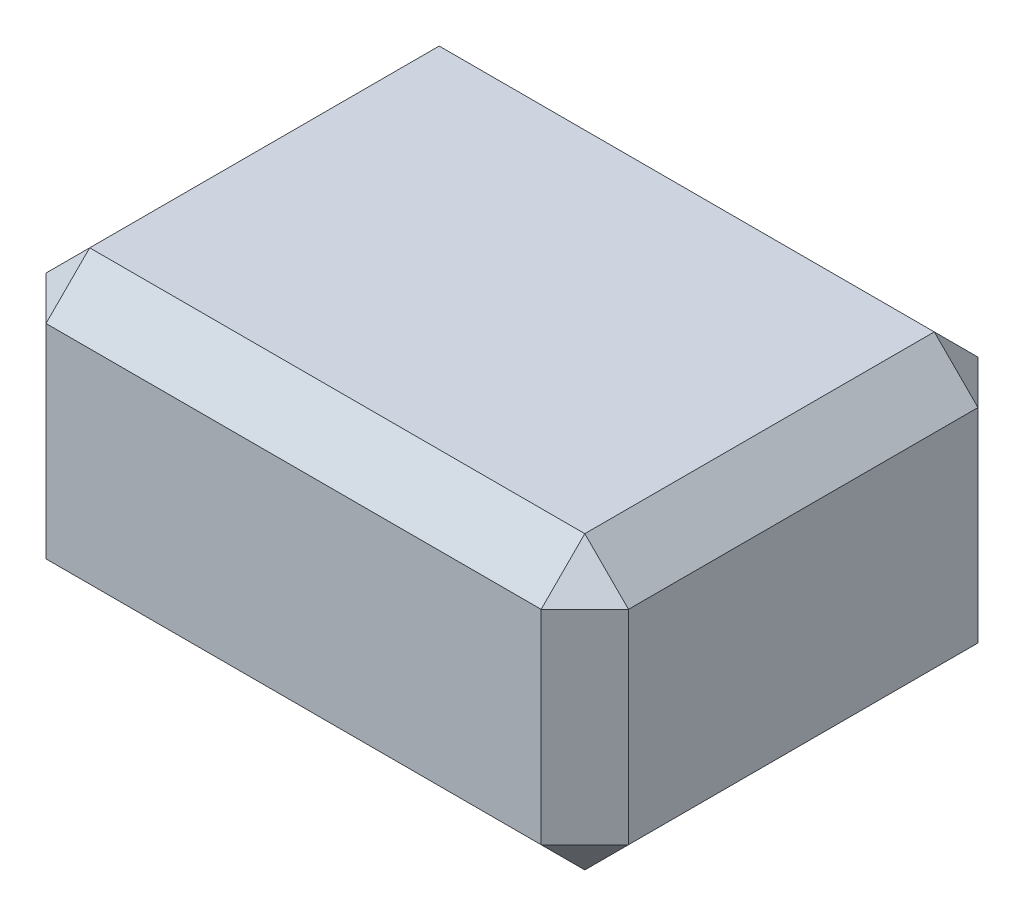
SolidWorks part; units mm, degrees
ref_plane "Front Plane" through (0, 0, 0) normal (0, 0, 1) x (1, 0, 0)
ref_plane "Top Plane" through (0, 0, 0) normal (0, 1, 0) x (1, 0, 0)
ref_plane "Right Plane" through (0, 0, 0) normal (1, 0, 0) x (0, 0, -1)
sketch "Sketch1" plane through (0, 0, 0) normal (0, 1, 0) x (1, 0, 0)
  line L0 (-20, -15) -> (20, -15)
  line L1 (20, -15) -> (20, 15)
  line L2 (20, 15) -> (-20, 15)
  line L3 (-20, 15) -> (-20, -15)
extrude "Boss-Extrude1" add sketch "Sketch1" along normal blind 20
chamfer "Chamfer1" distance 3 angle 45 12 edges at (-20, 0, 0) (0, 0, 15) (20, 0, 0) (0, 0, -15) (-20, 20, 0) (-20, 10, -15) (0, 20, -15) (20, 10, -15) (20, 20, 0) (20, 10, 15) (0, 20, 15) (-20, 10, 15)
